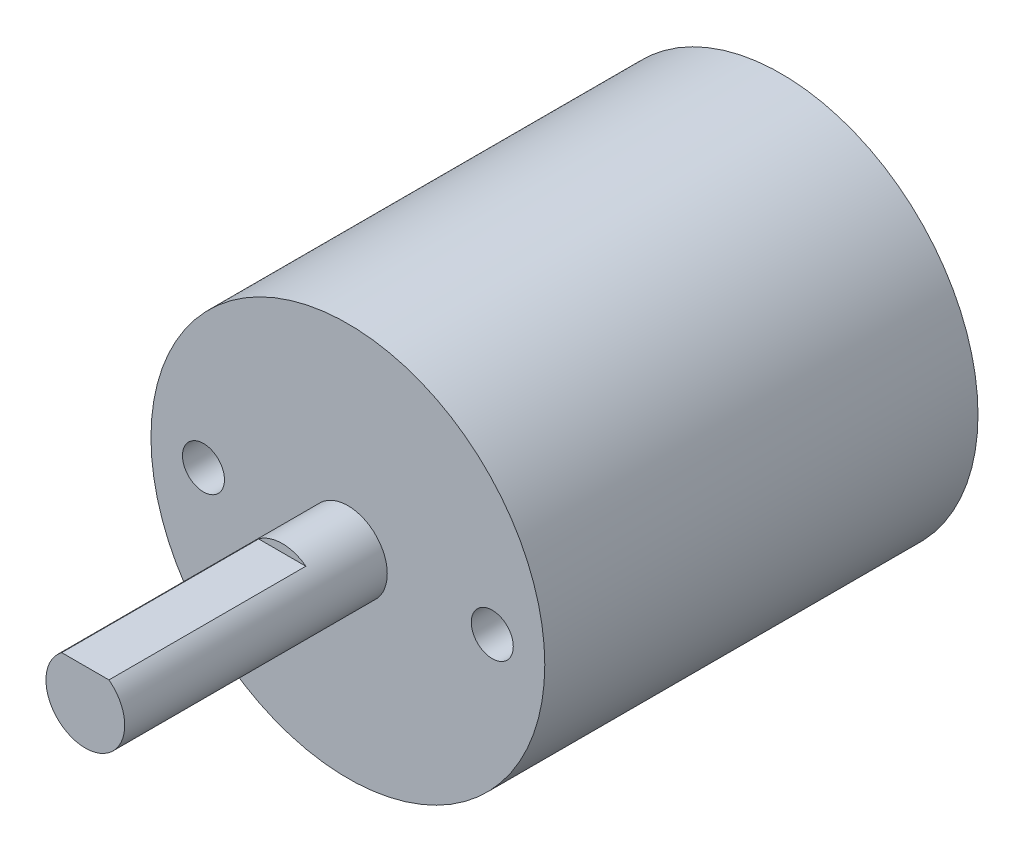
SolidWorks part; units mm, degrees
ref_plane "前视基准面" through (0, 0, 0) normal (0, 0, 1) x (1, 0, 0)
ref_plane "上视基准面" through (0, 0, 0) normal (0, 1, 0) x (1, 0, 0)
ref_plane "右视基准面" through (0, 0, 0) normal (1, 0, 0) x (0, 0, -1)
sketch "草图1" plane through (0, 0, 0) normal (0, 0, 1) x (1, 0, 0)
  circle A0 centre (0, 0) radius 7.5
extrude "凸台-拉伸1" add sketch "草图1" along normal blind 16.5
sketch "草图2" plane through (0, 0, 16.5) normal (0, 0, 1) x (1, 0, 0)
  circle A0 centre (0, 0) radius 1.5
extrude "凸台-拉伸2" add sketch "草图2" along normal blind 10
sketch "草图3" plane through (0, 0, 26.5) normal (0, 0, 1) x (1, 0, 0)
  line L0 (0, 1.5) -> (0, 1.2) construction
  line L1 (0, 1.2) -> (2.1676, 1.2) construction
  line L2 (2.1676, 1.2) -> (-1.6312, 1.2)
  line L3 (-1.6312, 1.2) -> (-1.6312, 1.7112)
  line L4 (-1.6312, 1.7112) -> (2.1676, 1.7112)
  line L5 (2.1676, 1.7112) -> (2.1676, 1.2)
  circle A0 centre (0, 0) radius 1.5 construction
extrude "切除-拉伸1" cut sketch "草图3" against normal blind 7.5
sketch "草图4" plane through (0, 0, 16.5) normal (0, 0, 1) x (1, 0, 0)
  circle A0 centre (0, 0) radius 5.5 construction
  circle A1 centre (5.5, 0) radius 1
  circle A2 centre (-5.5, 0) radius 1
hole_wizard "M2 螺纹孔1" positions "3D草图1" profile "草图5" tap size "M2" standard "GB"
sketch3d "3D草图1"
  point P0 (5.5, 0, 16.5)
  point P3 (-5.5, 0, 16.5)
sketch "草图5" plane through (5.5, 0, 16.5) normal (1, 0, 0) x (0, -1, 0)
  line L0 (0, 0) -> (0, 6.4619)
  line L1 (0, 6.4619) -> (0.8, 6)
  line L2 (0.8, 6) -> (0.8, 0)
  line L5 (0.8, 0) -> (0, 0)
  line L10 (0, 6.4619) -> (-0.8, 6) construction
  line L11 (0, -6.35) -> (0, 107.95) construction
  dimension "螺纹孔钻头直径" = 1.6
  dimension "螺纹孔钻头深度" = 6
  dimension "导头角度" = 120
cosmetic thread "孔螺蚊线1" parameters "D1"=4, "D2"=2
cosmetic thread "孔螺蚊线2" parameters "D1"=4, "D2"=2
